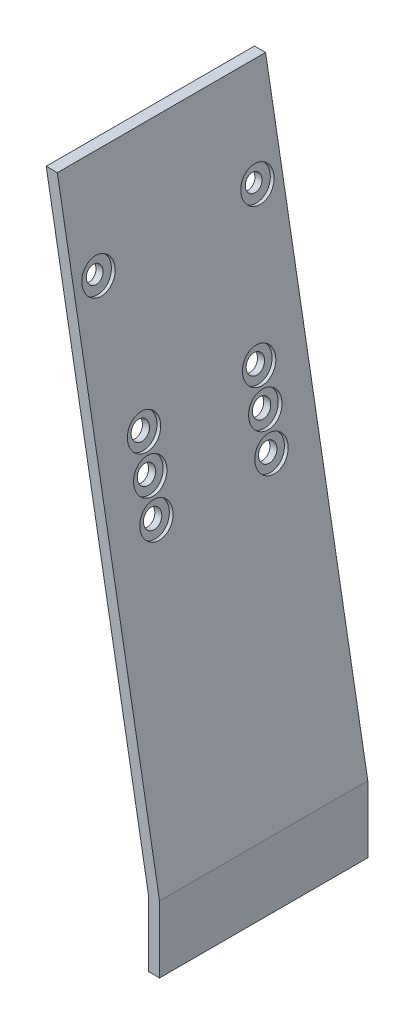
SolidWorks part; units mm, degrees
ref_plane "前视基准面" through (0, 0, 0) normal (0, 0, 1) x (1, 0, 0)
ref_plane "上视基准面" through (0, 0, 0) normal (0, 1, 0) x (1, 0, 0)
ref_plane "右视基准面" through (0, 0, 0) normal (1, 0, 0) x (0, 0, -1)
sketch "草图1" plane through (0, 0, 0) normal (0, 0, 1) x (1, 0, 0)
  line L1 (-1.462, -87.7087) -> (18.538, -87.7087) construction
  line L2 (18.538, -87.7087) -> (18.538, -75.7087)
  line L3 (18.538, -75.7087) -> (-3.1502, 47.2913)
  line L4 (-3.1502, 47.2913) -> (-1.1193, 47.2913)
  line L5 (-1.1193, 47.2913) -> (20.538, -75.5337)
  line L6 (20.538, -75.5337) -> (20.538, -87.7087)
  line L7 (20.538, -87.7087) -> (18.538, -87.7087)
  line L8 (7.2509, -11.6962) -> (-8.6277, -14.4961)
  dimension "D1" = 65
  dimension "D2" = 12
  dimension "D3" = 2
  dimension "164" = 170
  dimension "D7" = 135
  dimension "D8" = 2
extrude "凸台-拉伸1" add sketch "草图1" along normal blind 39 contours L5 L6 L7 L2 L3 L4
sketch "草图7" plane through (7.0017, 1.2346, 0) normal (0.9848, 0.1736, 0) x (0, 0, -1)
  line L0 (-39, 46.7672) -> (0, 46.7672) construction
  line L2 (-39, 46.7672) -> (-39, -77.9526) construction
  line L4 (0, 46.7672) -> (0, -77.9526) construction
  circle A0 centre (-30, -19.2328) radius 1.65
  circle A1 centre (-9, -19.2328) radius 1.65
  circle A3 centre (-30, -12.7328) radius 1.65
  circle A4 centre (-9, -12.7328) radius 1.65
  circle A5 centre (-9, -25.7328) radius 1.65
  circle A6 centre (-30, -25.7328) radius 1.65
  dimension "D1" = 3.3
  dimension "D2" = 3.3
  dimension "D5" = 66
  dimension "D7" = 3.3
  dimension "D8" = 3.3
  dimension "D9" = 6.5
  dimension "D10" = 6.5
  dimension "D11" = 6.5
  dimension "D12" = 6.5
  dimension "D13" = 3.3
  dimension "D14" = 3.3
  dimension "D15" = 9
  dimension "D16" = 9
  dimension "D17" = 9
  dimension "D18" = 9
  dimension "D3" = 9
  dimension "D4" = 9
  dimension "D6" = 66
sketch "草图11" plane through (5.0321, 0.8873, 0) normal (-0.9848, -0.1736, 0) x (0, 0, 1)
  line L0 (39, 47.1198) -> (0, 47.1198) construction
  line L1 (39, -77.7776) -> (39, 47.1198) construction
  line L2 (0, -77.7776) -> (0, 47.1198) construction
  circle A0 centre (5, 12.1198) radius 1.5
  circle A1 centre (34, 12.1198) radius 1.5
  dimension "D3" = 3
  dimension "D4" = 3
  dimension "D2" = 5
  dimension "D5" = 35
  dimension "D6" = 5
  dimension "D1" = 35
extrude "切除-拉伸1" cut sketch "草图7" against normal blind 10
extrude "切除-拉伸2" cut sketch "草图11" against normal blind 10
sketch "草图12" plane through (0, 0, 39) normal (0, 0, 1) x (1, 0, 0)
  line L5 (-14.1657, 52.0792) -> (14.8434, 52.0792)
  line L6 (-14.1657, 52.0792) -> (-14.1657, 42.0792)
  line L7 (-14.1657, 42.0792) -> (14.8434, 42.0792)
  line L8 (14.8434, 52.0792) -> (14.8434, 42.0792)
  dimension "D1" = 10
extrude "切除-拉伸3" cut sketch "草图12" against normal blind 40
sketch "草图14" plane through (7.0017, 1.2346, 0) normal (0.9848, 0.1736, 0) x (0, 0, -1)
  circle A0 centre (-34, 12.1198) radius 3
  circle A1 centre (-5, 12.1198) radius 3
  circle A2 centre (-30, -19.2328) radius 3
  circle A3 centre (-9, -19.2328) radius 3
  circle A4 centre (-30, -12.7328) radius 3
  circle A5 centre (-9, -12.7328) radius 3
  circle A7 centre (-30, -25.7328) radius 3
  circle A8 centre (-9, -25.7328) radius 3
extrude "切除-拉伸4" cut sketch "草图14" against normal blind 0.7
ref_plane "基准面1" through (-2.2312, 42.0792, 39) normal (-0.1736, 0.9848, 0) x (0.9848, 0.1736, 0)
ref_plane "基准面2" through (-0.2003, 42.0792, 39) normal (0.1736, -0.9848, 0) x (-0.9848, -0.1736, 0)
sketch "草图17" plane through (0, 0, 0) normal (0, 0, -1) x (-1, 0, 0)
  line L1 (-8.851, 49.5962) -> (13.545, 49.5962)
  line L2 (-8.851, 49.5962) -> (-8.851, 30.2198)
  line L3 (-8.851, 30.2198) -> (13.545, 30.2198)
  line L4 (13.545, 49.5962) -> (13.545, 30.2198)
extrude "切除-拉伸5" cut sketch "草图17" against normal blind 48
sketch "草图18" plane through (0, 30.2198, 0) normal (0, 1, 0) x (1, 0, 0)
  line L0 (1.8908, -39) -> (-0.14, -39) construction
  line L1 (-20.3699, 0) -> (28.5854, 0)
  line L2 (-20.3699, 0) -> (-20.3699, -0.5)
  line L3 (-20.3699, -0.5) -> (28.5854, -0.5)
  line L4 (28.5854, 0) -> (28.5854, -0.5)
  line L5 (-11.5714, -38.5) -> (28.5854, -38.5)
  line L6 (-11.5714, -38.5) -> (-11.5714, -39)
  line L7 (-11.5714, -39) -> (28.5854, -39)
  line L8 (28.5854, -38.5) -> (28.5854, -39)
  line L9 (1.8908, 0) -> (20.538, 0) construction
  dimension "D1" = 0
  dimension "D2" = 0
  dimension "D3" = 0.5
  dimension "D4" = 0.5
extrude "切除-拉伸6" cut sketch "草图18" against normal blind 150
